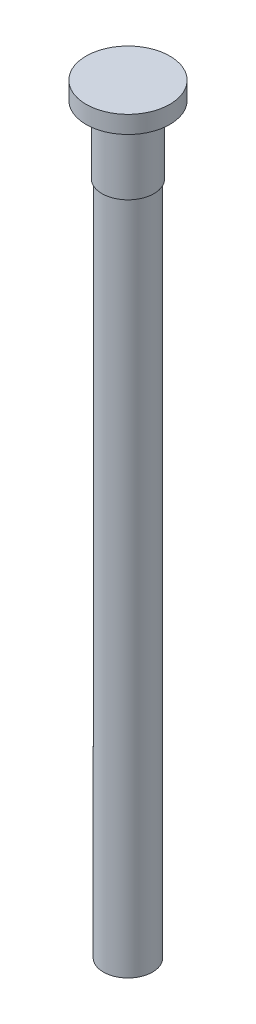
SolidWorks part; units mm, degrees
material "Plain Carbon Steel"
ref_plane "Front Plane" through (0, 0, 0) normal (0, 0, 1) x (1, 0, 0)
ref_plane "Top Plane" through (0, 0, 0) normal (0, 1, 0) x (1, 0, 0)
ref_plane "Right Plane" through (0, 0, 0) normal (1, 0, 0) x (0, 0, -1)
sketch "Sketch1" plane through (0, 0, 0) normal (0, 1, 0) x (1, 0, 0)
  circle A0 centre (0, 0) radius 2.9464
  dimension "D1" = 5.8928
extrude "Boss-Extrude1" add sketch "Sketch1" against normal blind 89.0143
sketch "Sketch2" plane through (0, 0, 0) normal (0, 1, 0) x (1, 0, 0)
  circle A0 centre (0, 0) radius 5.0165
  circle A1 centre (0, 0) radius 2.9464 construction
  dimension "D1" = 10.033
extrude "Boss-Extrude2" add sketch "Sketch2" along normal blind 2.0955
sketch "Sketch3" plane through (0, 0, 0) normal (0, -1, 0) x (1, 0, 0)
  circle A0 centre (0, 0) radius 3.1115
  dimension "D1" = 6.223
extrude "Boss-Extrude3" add sketch "Sketch3" along normal blind 8.128
